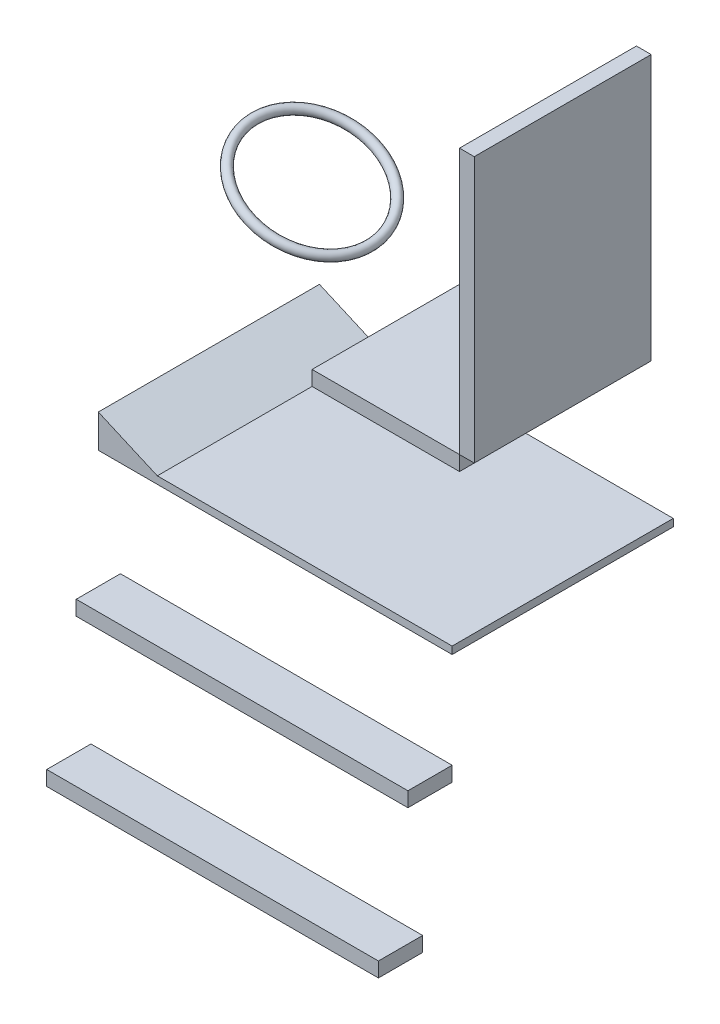
SolidWorks part; units mm, degrees
ref_plane "Right Plane" through (0, 0, 0) normal (0, 0, 1) x (1, 0, 0)
ref_plane "Top Plane" through (0, 0, 0) normal (0, 1, 0) x (1, 0, 0)
ref_plane "Front Plane" through (0, 0, 0) normal (1, 0, 0) x (0, 0, -1)
ref_plane "Step 1 top 18in" through (0, 457.2, 0) normal (0, 1, 0) x (1, 0, 0)
ref_plane "Step 2 top 18in" through (0, 914.4, 0) normal (0, 1, 0) x (1, 0, 0)
ref_plane "Truck Floor 50in from ground" through (0, 1270, 0) normal (0, 1, 0) x (1, 0, 0)
ref_plane "Seat Bottom" through (0, 1778, 0) normal (0, 1, 0) x (1, 0, 0)
ref_plane "Steering Wheel Center Height" through (0, 2032, 0) normal (0, 1, 0) x (1, 0, 0)
ref_plane "Center Plane" through (0, 0, -381) normal (0, 0, 1) x (1, 0, 0)
sketch "Floor Dimensions" plane through (0, 1270, 0) normal (0, 1, 0) x (1, 0, 0)
  line L5 (0, 762) -> (0, 0)
  line L7 (0, 0) -> (1219.2, 0)
  line L8 (-670.56, 0) -> (670.56, 0) construction
  line L9 (1219.2, 0) -> (1219.2, 762)
  line L10 (1219.2, 762) -> (0, 762)
  point P0 (0, 0)
  point P3 (0, 381)
  dimension "D1" = 1219.2
  dimension "D2" = 762
sketch "Step 2" plane through (0, 914.4, 0) normal (0, 1, 0) x (1, 0, 0)
  line L0 (1219.2, 0) -> (1219.2, 762) construction
  line L1 (76.2, -152.4) -> (1219.2, -152.4)
  line L2 (76.2, -152.4) -> (76.2, 0)
  line L3 (76.2, 0) -> (1219.2, 0)
  line L4 (1219.2, -152.4) -> (1219.2, 0)
  line L5 (0, 0) -> (1219.2, 0) construction
  dimension "D1" = 1143
  dimension "D2" = 152.4
  dimension "D3" = 152.4
sketch "Sketch4" plane through (0, 457.2, 0) normal (0, 1, 0) x (1, 0, 0)
  line L0 (1219.2, -152.4) -> (1219.2, 0) construction
  line L1 (1219.2, -101.6) -> (76.2, -101.6)
  line L2 (1219.2, -101.6) -> (1219.2, -254)
  line L3 (1219.2, -254) -> (76.2, -254)
  line L4 (76.2, -101.6) -> (76.2, -254)
  line L5 (76.2, -152.4) -> (1219.2, -152.4) construction
  dimension "D1" = 152.4
  dimension "D2" = 101.6
extrude "Step-2" add sketch "Step 2" against normal blind 50.8
extrude "Step-1" add sketch "Sketch4" against normal blind 50.8 separate body
sketch "Sketch5" plane through (0, 1778, 0) normal (0, 1, 0) x (1, 0, 0)
  line L0 (660.4, 76.2) -> (660.4, 685.8)
  line L1 (660.4, 76.2) -> (1168.4, 76.2)
  line L2 (660.4, 685.8) -> (1168.4, 685.8)
  line L3 (1168.4, 76.2) -> (1168.4, 685.8)
  line L4 (660.4, 76.2) -> (1168.4, 685.8) construction
  line L5 (660.4, 685.8) -> (1168.4, 76.2) construction
  line L6 (-670.56, 381) -> (670.56, 381) construction
  line L7 (0, 762) -> (0, 0) construction
  point P1 (914.4, 381)
  dimension "D1" = 609.6
  dimension "D2" = 660.4
  dimension "D3" = 508
extrude "Seat-Bottom" add sketch "Sketch5" against normal blind 50.8 separate body
sketch "Sketch6" plane through (0, 0, -381) normal (0, 0, 1) x (1, 0, 0)
  line L0 (1219.2, 1778) -> (1219.2, 2692.4)
  line L7 (1168.4, 1778) -> (1168.4, 2692.4)
  line L8 (1219.2, 2692.4) -> (1168.4, 2692.4)
  line L9 (1168.4, 1778) -> (1219.2, 1778)
  line L10 (558.8, 1778) -> (-558.8, 1778) construction
  dimension "D1" = 914.4
  dimension "D2" = 1219.2
extrude "Seat-Back" add sketch "Sketch6" along normal up to vertex (304.8 mm away) and the other way up to vertex (304.8 mm away) separate body
sketch "Sketch7" plane through (0, 0, -381) normal (0, 0, 1) x (1, 0, 0)
  line L0 (0, 1358.9) -> (203.2, 1270)
  line L1 (0, -55) -> (0, 55) construction
  line L2 (0, 1270) -> (1219.2, 1270) construction
  line L3 (203.2, 1270) -> (1219.2, 1270)
  line L4 (1219.2, 1270) -> (0, 1270) construction
  line L5 (1219.2, 1270) -> (1219.2, 1244.6)
  line L6 (1219.2, 1244.6) -> (0, 1244.6)
  line L7 (0, 1244.6) -> (0, 1358.9)
  line L8 (660.4, 1727.2) -> (660.4, 1778) construction
  dimension "D1" = 25.4
  dimension "D2" = 457.2
  dimension "D3" = 88.9
extrude "Floor" add sketch "Sketch7" along normal up to vertex (381 mm away) and the other way up to vertex (381 mm away) separate body up to point (1219.2, 1270, 0) other way up to point (1219.2, 1270, -762)
sketch "Steering-tilt" plane through (0, 2032, 0) normal (0, 1, 0) x (1, 0, 0)
  line L0 (355.6, 762) -> (355.6, 0) construction
  line L1 (1219.2, 762) -> (0, 762) construction
  line L2 (0, 0) -> (1219.2, 0) construction
  line L3 (660.4, 685.8) -> (660.4, 76.2) construction
  dimension "D1" = 304.8
ref_plane "Steering Wheel Plane" through (841.8135, 1805.2749, 0) normal (-0.4226, -0.9063, 0) x (0, 0, 1)
sketch "Wheel Center" plane through (841.8135, 1805.2749, 0) normal (-0.4226, -0.9063, 0) x (0, 0, 1)
  circle A0 centre (-381, 536.7252) radius 217.4875
  dimension "D1" = 434.975
sketch "Sketch12" plane through (0, 0, -381) normal (0, 0, 1) x (1, 0, 0)
  line L0 (158.2647, 2124.019) -> (552.4859, 1940.1906) construction
  line L1 (461.9799, 1982.3942) -> (1221.6471, 1628.1556) construction
  circle A0 centre (158.2647, 2124.019) radius 15.875
  dimension "D1" = 31.75
sweep "Sweep1" add profiles "Sketch12" path "Wheel Center"
